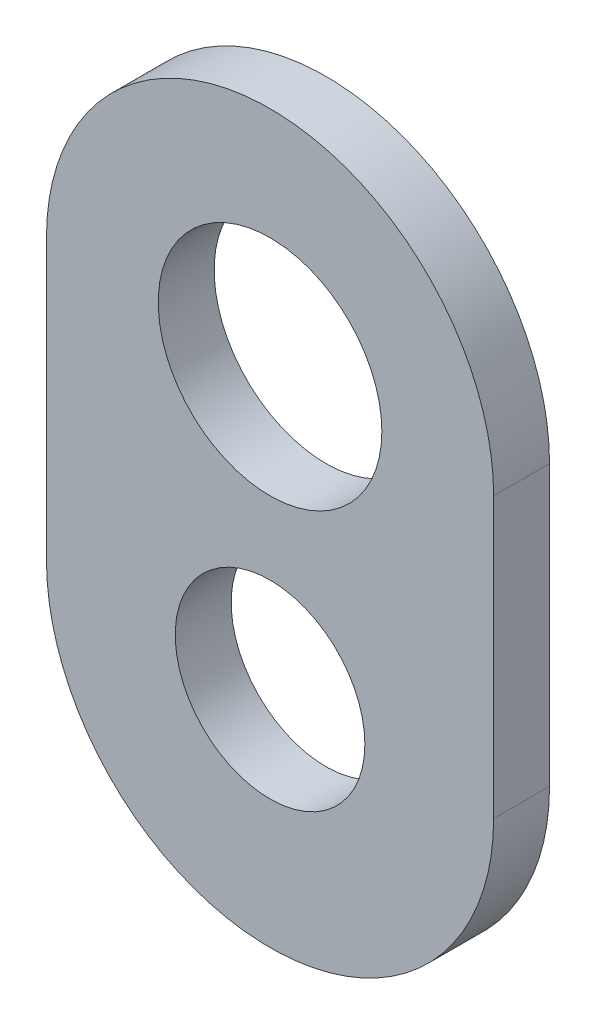
SolidWorks part; units mm, degrees
ref_plane "Front Plane" through (0, 0, 0) normal (0, 0, 1) x (1, 0, 0)
ref_plane "Top Plane" through (0, 0, 0) normal (0, 1, 0) x (1, 0, 0)
ref_plane "Right Plane" through (0, 0, 0) normal (1, 0, 0) x (0, 0, -1)
sketch "Sketch1" plane through (0, 0, 0) normal (0, 0, 1) x (1, 0, 0)
  line L0 (-25.4, 0) -> (-25.4, -31.75)
  line L1 (25.4, 0) -> (25.4, -31.75)
  circle A0 centre (0, 0) radius 12.7
  circle A2 centre (0, -31.75) radius 10.7696
  arc A3 (-25.4, -31.75) -> (25.4, -31.75) centre (0, -31.75) ccw
  arc A4 (25.4, 0) -> (-25.4, 0) centre (0, 0) ccw
  dimension "D1" = 25.4
  dimension "D2" = 50.8
  dimension "D4" = 50.8
  dimension "D5" = 21.5392
  dimension "D3" = 31.75
extrude "Boss-Extrude1" add sketch "Sketch1" along normal blind 6.35
